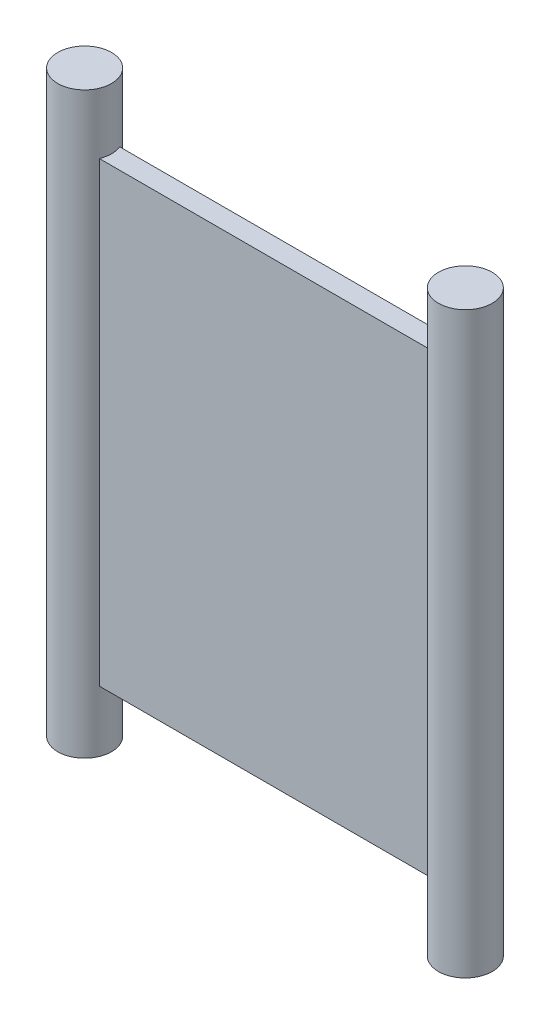
SolidWorks part; units mm, degrees
ref_plane "Front Plane" through (0, 0, 0) normal (0, 0, 1) x (1, 0, 0)
ref_plane "Top Plane" through (0, 0, 0) normal (0, 1, 0) x (1, 0, 0)
ref_plane "Right Plane" through (0, 0, 0) normal (1, 0, 0) x (0, 0, -1)
sketch "Sketch1" plane through (0, 0, 0) normal (0, 1, 0) x (1, 0, 0)
  line L1 (9.373, 0.5) -> (-9.373, 0.5)
  line L2 (9.373, 0.5) -> (9.373, -0.5)
  line L3 (9.373, -0.5) -> (-9.373, -0.5)
  line L4 (-9.373, 0.5) -> (-9.373, -0.5)
  line L5 (9.373, 0.5) -> (-9.373, -0.5) construction
  line L6 (9.373, -0.5) -> (-9.373, 0.5) construction
  point P0 (0, 0)
  dimension "D1" = 18.746
  dimension "D3" = 1
extrude "Boss-Extrude1" add sketch "Sketch1" along normal blind 22.5
ref_plane "Plane1" through (0, 11.25, 0) normal (0, 1, 0) x (1, 0, 0)
sketch "Sketch2" plane through (0, 11.25, 0) normal (0, 1, 0) x (1, 0, 0)
  line L0 (9.373, -0.5) -> (9.373, 0.5) construction
  line L1 (-9.373, 0.5) -> (-9.373, -0.5) construction
  line L2 (9.373, -0.5) -> (9.373, 0.5) construction
  line L3 (-9.373, 0.5) -> (-9.373, -0.5) construction
  circle A0 centre (-9.373, 0) radius 1.325
  circle A1 centre (9.373, 0) radius 1.325
  dimension "D1" = 2.65
extrude "Boss-Extrude2" add sketch "Sketch2" along normal mid plane 28.5
